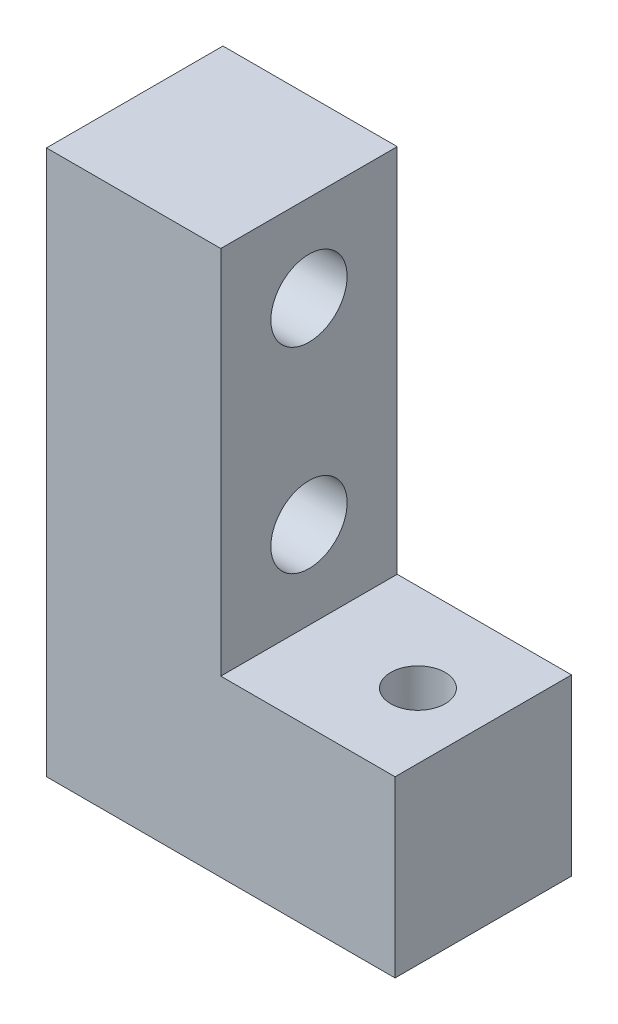
SolidWorks part; units mm, degrees
ref_plane "Plan de face" through (0, 0, 0) normal (0, 0, 1) x (1, 0, 0)
ref_plane "Plan de dessus" through (0, 0, 0) normal (0, 1, 0) x (1, 0, 0)
ref_plane "Plan de droite" through (0, 0, 0) normal (1, 0, 0) x (0, 0, -1)
sketch "Esquisse1" plane through (0, 0, 0) normal (0, 0, 1) x (1, 0, 0)
  line L1 (0, 0) -> (16, 0)
  line L2 (0, 0) -> (0, 25)
  line L3 (0, 25) -> (16, 25)
  line L4 (16, 0) -> (16, 25)
  dimension "D1" = 16
  dimension "D2" = 25
extrude "Boss.-Extru.1" add sketch "Esquisse1" along normal blind 8.1
sketch "Esquisse2" plane through (0, 0, 0) normal (0, -1, 0) x (1, 0, 0)
  line L0 (8, 8.1) -> (8, 0) construction
  line L1 (0, 8.1) -> (16, 8.1) construction
  line L2 (0, 0) -> (16, 0) construction
  line L3 (16, 4.05) -> (0, 4.05) construction
  line L4 (16, 8.1) -> (16, 0) construction
  line L5 (0, 8.1) -> (0, 0) construction
  circle A0 centre (3, 4.05) radius 1.25
  circle A1 centre (13, 4.05) radius 1.25
  dimension "D1" = 10
  dimension "D2" = 2.5
extrude "Enlèv. mat.-Extru.1" cut sketch "Esquisse2" against normal blind 8
sketch "Esquisse3" plane through (0, 0, 0) normal (-1, 0, 0) x (0, 0, 1)
  line L0 (4.05, 0) -> (4.05, 21) construction
  line L1 (8.1, 0) -> (0, 0) construction
  circle A0 centre (4.05, 21) radius 1.75
  circle A1 centre (4.05, 12) radius 1.75
  dimension "D1" = 3.5
  dimension "D2" = 9
  dimension "D3" = 12
extrude "Enlèv. mat.-Extru.2" cut sketch "Esquisse3" against normal blind 8
sketch "Esquisse4" plane through (0, 0, 8.1) normal (0, 0, 1) x (1, 0, 0)
  line L0 (0, 25) -> (0, 0) construction
  line L1 (16, 25) -> (8, 25)
  line L2 (16, 25) -> (16, 8)
  line L3 (16, 8) -> (8, 8)
  line L4 (8, 25) -> (8, 8)
  line L5 (0, 0) -> (16, 0) construction
  dimension "D1" = 8
  dimension "D2" = 8
extrude "Enlèv. mat.-Extru.3" cut sketch "Esquisse4" against normal through all
